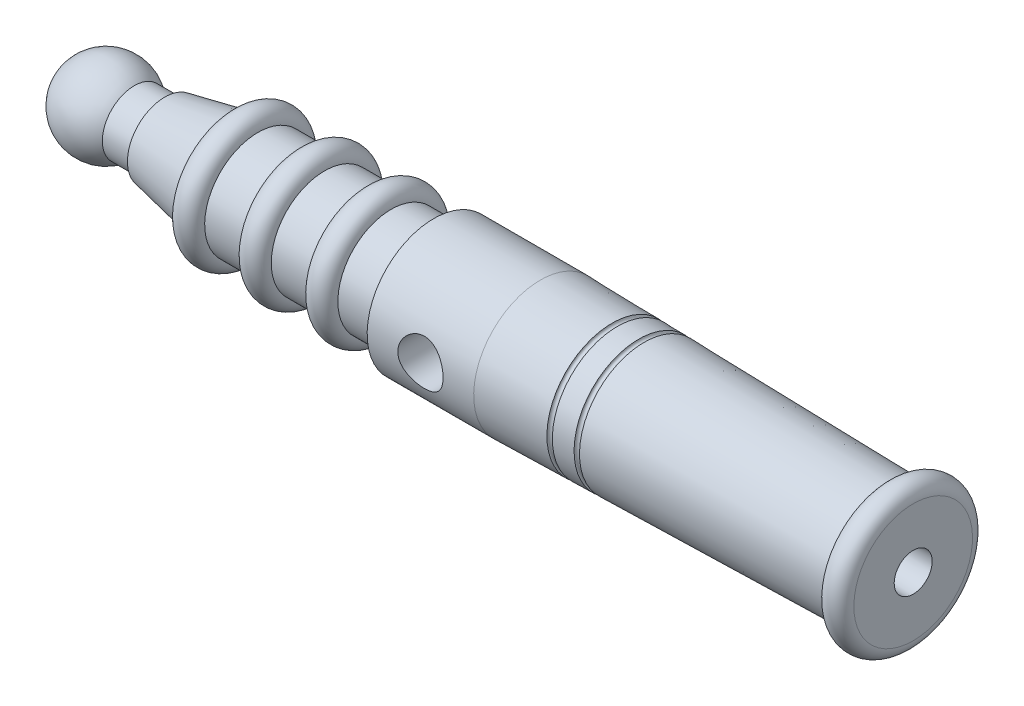
SolidWorks part; units mm, degrees
ref_plane "Front Plane" through (0, 0, 0) normal (0, 0, 1) x (1, 0, 0)
ref_plane "Top Plane" through (0, 0, 0) normal (0, 1, 0) x (1, 0, 0)
ref_plane "Right Plane" through (0, 0, 0) normal (1, 0, 0) x (0, 0, -1)
sketch "Sketch1" plane through (0, 0, 0) normal (0, 0, 1) x (1, 0, 0)
  line L0 (0, 0) -> (109.5027, 0)
  line L1 (109.5027, 0) -> (109.5027, 2.9959)
  line L2 (109.5027, 2.9959) -> (159.4995, 3.5638)
  line L3 (159.4995, 3.5638) -> (159.4995, 11.1404)
  line L4 (154.5, 11.1907) -> (108.9697, 12.1078)
  line L5 (89.5, 12.5) -> (69.5, 12.5)
  line L6 (69.5, 12.5) -> (69.5, 10)
  line L9 (19, 6) -> (13.2915, 6)
  line L10 (69.5, 10) -> (61.5, 10)
  line L12 (19, 6) -> (19, 7)
  line L13 (19, 7) -> (31.5485, 9.5097)
  line L14 (44, 10) -> (36.5, 10)
  line L15 (56.5, 10) -> (49, 10)
  line L16 (102.9701, 12.2287) -> (89.5, 12.5)
  line L17 (107.9701, 12.128) -> (103.9697, 12.2085)
  arc A1 (159.4995, 11.1404) -> (154.5, 11.1907) centre (156.9995, 11.1404) ccw
  arc A2 (0, 0) -> (13.2915, 6) centre (8, 0) cw
  arc A3 (61.5, 10) -> (56.5, 10) centre (59, 10) ccw
  arc A4 (49, 10) -> (44, 10) centre (46.5, 10) ccw
  arc A5 (36.5, 10) -> (31.5485, 9.5097) centre (34, 10) ccw
  arc A6 (108.9697, 12.1078) -> (107.9701, 12.128) centre (108.4697, 12.1078) cw
  arc A7 (103.9697, 12.2085) -> (102.9701, 12.2287) centre (103.4697, 12.2085) cw
  dimension "D3" = 2.5
  dimension "D9" = 8
  dimension "D15" = 2.5
  dimension "D19" = 0.5
  dimension "D1" = 50
  dimension "D4" = 2.9959
  dimension "D5" = 65
  dimension "D6" = 20
  dimension "D7" = 35.5
  dimension "D8" = 11
  dimension "D10" = 6
  dimension "D11" = 15
  dimension "D12" = 10
  dimension "D13" = 7
  dimension "D14" = 12.5
  dimension "D16" = 8
  dimension "D17" = 10
  dimension "D18" = 20
  dimension "D20" = 5
revolve "Revolve2" add sketch "Sketch1" angle 360 about L0
sketch "Sketch2" plane through (0, 0, 0) normal (0, 0, 1) x (1, 0, 0)
  line L0 (69.5, 12.5) -> (69.5, -12.5) construction
  circle A0 centre (79.5, 0) radius 4.25
  point P4 (0, 0)
  dimension "D1" = 8.5
  dimension "D2" = 10
extrude "Cut-Extrude1" cut sketch "Sketch2" against normal through all both and the other way through all
